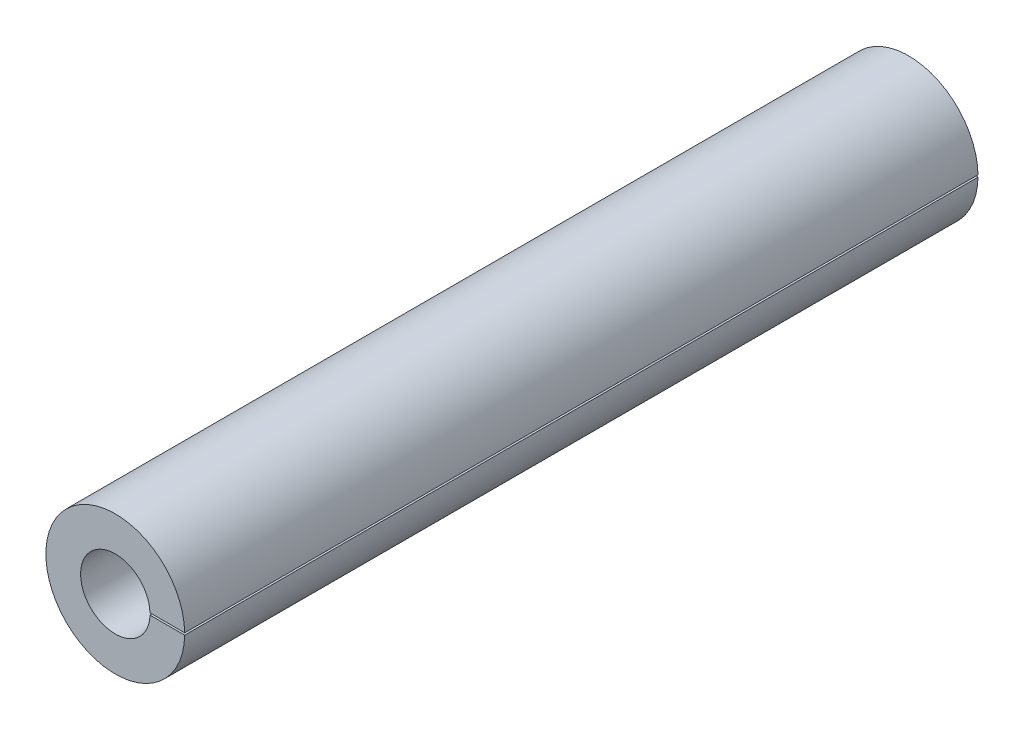
SolidWorks part; units mm, degrees
ref_plane "Plan1" through (0, 0, 0) normal (0, 0, 1) x (1, 0, 0)
ref_plane "Plan2" through (0, 0, 0) normal (0, 1, 0) x (1, 0, 0)
ref_plane "Plan3" through (0, 0, 0) normal (1, 0, 0) x (0, 0, -1)
sketch "Esquisse1" plane through (0, 0, 0) normal (0, 0, 1) x (1, 0, 0)
  circle A0 centre (0, 0) radius 70
extrude "Base-Extrusion" add sketch "Esquisse1" along normal blind 800
sketch "Esquisse2" plane through (0, 0, 800) normal (0, 0, 1) x (1, 0, 0)
  circle A0 centre (0, 0) radius 35
extrude "Enlèv. mat.-Extru.1" cut sketch "Esquisse2" against normal blind 800
sketch "Esquisse3" plane through (0, 0, 800) normal (0, 0, 1) x (1, 0, 0)
  line L1 (10, -1) -> (80, -1)
  line L2 (10, -1) -> (10, 1)
  line L3 (10, 1) -> (80, 1)
  line L4 (80, -1) -> (80, 1)
extrude "Enlèv. mat.-Extru.2" cut sketch "Esquisse3" against normal blind 800
